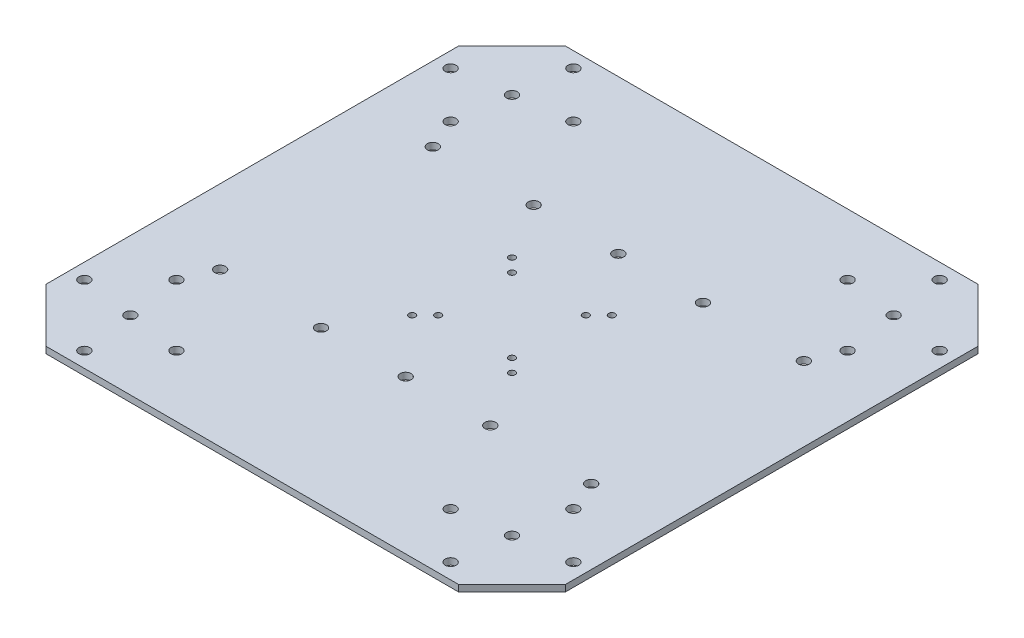
SolidWorks part; units mm, degrees
ref_plane "Front Plane" through (0, 0, 0) normal (0, 0, 1) x (1, 0, 0)
ref_plane "Top Plane" through (0, 0, 0) normal (0, 1, 0) x (1, 0, 0)
ref_plane "Right Plane" through (0, 0, 0) normal (1, 0, 0) x (0, 0, -1)
sketch "Sketch1" plane through (0, 0, 0) normal (0, 1, 0) x (1, 0, 0)
  line L0 (-72.7246, 121.6334) -> (117.2754, 121.6334)
  line L1 (117.2754, 121.6334) -> (142.0241, 96.8847)
  line L2 (142.0241, 96.8847) -> (142.0241, -93.1153)
  line L3 (142.0241, -93.1153) -> (117.2754, -117.864)
  line L4 (117.2754, -117.864) -> (-72.7246, -117.864)
  line L5 (-72.7246, -117.864) -> (-97.4734, -93.1153)
  line L6 (-97.4734, -93.1153) -> (-97.4734, 96.8847)
  line L7 (-97.4734, 96.8847) -> (-72.7246, 121.6334)
  dimension "D1" = 190
  dimension "D2" = 135
  dimension "D3" = 135
  dimension "D4" = 35
extrude "Boss-Extrude1" add sketch "Sketch1" along normal blind 3
sketch "Sketch2" plane through (0, 3, 0) normal (0, 1, 0) x (1, 0, 0)
  line L0 (-97.4734, -93.1153) -> (-58.5825, -54.2244)
  line L1 (-58.5825, -54.2244) -> (-33.8338, -78.9732)
  line L2 (-33.8338, -78.9732) -> (-72.7246, -117.864)
  line L3 (142.0241, -93.1153) -> (106.6439, -53.574)
  line L4 (106.6439, -53.574) -> (80.601, -76.8764)
  line L5 (80.601, -76.8764) -> (117.2754, -117.864)
  line L6 (117.2754, 121.6334) -> (77.828, 85.6472)
  line L7 (77.828, 85.6472) -> (101.3915, 59.8173)
  line L8 (101.3915, 59.8173) -> (142.0241, 96.8847)
  line L9 (-72.7246, 121.6334) -> (-36.0091, 80.6826)
  line L10 (-36.0091, 80.6826) -> (-62.0301, 57.3529)
  line L11 (-62.0301, 57.3529) -> (-97.4734, 96.8847)
  line L12 (-97.4734, -93.1153) -> (-72.7246, -117.864)
  line L13 (117.2754, -117.864) -> (142.0241, -93.1153)
  line L14 (117.2754, 121.6334) -> (142.0241, 96.8847)
  line L15 (-97.4734, 96.8847) -> (-72.7246, 121.6334)
  dimension "D1" = 55
  dimension "D2" = 90
  dimension "D3" = 55
  dimension "D4" = 90
  dimension "D5" = 55
  dimension "D6" = 90
  dimension "D7" = 90
  dimension "D8" = 55
  dimension "D9" = 90
extrude "Boss-Extrude2" add sketch "Sketch2" against normal blind 2
sketch "Sketch3" plane through (0, 3, 0) normal (0, 1, 0) x (1, 0, 0)
  line L0 (142.0241, -93.1153) -> (133.1853, -84.2765)
  line L1 (133.1853, -84.2765) -> (134.953, -82.5087)
  line L2 (134.953, -82.5087) -> (113.7398, -61.2955)
  line L3 (113.7398, -61.2955) -> (85.4556, -89.5798)
  line L4 (85.4556, -89.5798) -> (106.6688, -110.793)
  line L5 (117.2754, 121.6334) -> (108.4365, 112.7946)
  line L6 (108.4365, 112.7946) -> (106.6688, 114.5624)
  line L7 (106.6688, 114.5624) -> (85.4556, 93.3492)
  line L8 (85.4556, 93.3492) -> (113.7398, 65.0649)
  line L9 (113.7398, 65.0649) -> (134.953, 86.2781)
  line L10 (-72.7246, 121.6334) -> (-63.8858, 112.7946)
  line L11 (-63.8858, 112.7946) -> (-62.118, 114.5624)
  line L12 (-62.118, 114.5624) -> (-40.9048, 93.3492)
  line L13 (-40.9048, 93.3492) -> (-69.1891, 65.0649)
  line L14 (-69.1891, 65.0649) -> (-90.4023, 86.2781)
  line L15 (-42.6726, -87.812) -> (-40.9048, -89.5798)
  line L16 (-60.3503, -109.0252) -> (-62.118, -110.793)
  line L17 (-70.9569, -63.0633) -> (-69.1891, -61.2955)
  line L18 (-69.1891, -61.2955) -> (-67.4213, -63.0633)
  line L19 (-40.9048, -89.5798) -> (-42.6726, -91.3475)
  line L20 (-97.4734, -93.1153) -> (-88.6345, -84.2765)
  line L21 (-97.4734, -93.1153) -> (-72.7246, -117.864) construction
  line L22 (-88.6345, -84.2765) -> (-90.4023, -82.5087)
  circle A0 centre (134.953, -82.5087) radius 2.5
  circle A1 centre (113.7398, -61.2955) radius 2.5
  circle A2 centre (85.4556, -89.5798) radius 2.5
  circle A3 centre (106.6688, -110.793) radius 2.5
  circle A4 centre (106.6688, 114.5624) radius 2.5
  circle A5 centre (85.4556, 93.3492) radius 2.5
  circle A6 centre (113.7398, 65.0649) radius 2.5
  circle A7 centre (134.953, 86.2781) radius 2.5
  circle A9 centre (-40.9048, 93.3492) radius 2.5
  circle A10 centre (-69.1891, 65.0649) radius 2.5
  circle A11 centre (-90.4023, 86.2781) radius 2.5
  circle A13 centre (-69.1891, -61.2955) radius 2.5
  circle A14 centre (-40.9048, -89.5798) radius 2.5
  circle A15 centre (-62.118, -110.793) radius 2.5
  circle A16 centre (-62.118, 114.5624) radius 2.5
  circle A17 centre (-90.4023, -82.5087) radius 2.5
  dimension "D3" = 30
  dimension "D6" = 12.5
  dimension "D11" = 12.5
  dimension "D16" = 90
  dimension "D1" = 12.5
  dimension "D2" = 2.5
  dimension "D4" = 40
  dimension "D5" = 30
  dimension "D7" = 2.5
  dimension "D8" = 30
  dimension "D9" = 40
  dimension "D10" = 30
  dimension "D12" = 2.5
  dimension "D13" = 30
  dimension "D14" = 40
  dimension "D15" = 30
  dimension "D17" = 12.5
  dimension "D19" = 40
  dimension "D20" = 30
extrude "Cut-Extrude1" cut sketch "Sketch3" against normal blind 3
sketch "Sketch4" plane through (0, 3, 0) normal (0, 1, 0) x (1, 0, 0)
  line L0 (22.2754, 121.6334) -> (22.2754, 26.8847) construction
  line L1 (117.2754, 121.6334) -> (-72.7246, 121.6334) construction
  line L2 (-72.7246, -117.864) -> (117.2754, -117.864) construction
  line L3 (-97.4734, 1.8847) -> (-2.7246, 1.8847) construction
  line L4 (-97.4734, 96.8847) -> (-97.4734, -93.1153) construction
  line L5 (142.0241, -93.1153) -> (142.0241, 96.8847) construction
  line L6 (47.2754, 1.8847) -> (142.0241, 1.8847) construction
  line L7 (22.2754, -23.1153) -> (22.2754, -117.864) construction
  line L8 (-2.7246, -23.1153) -> (47.2754, -23.1153)
  line L9 (-2.7246, -23.1153) -> (-2.7246, 26.8847)
  line L10 (-2.7246, 26.8847) -> (47.2754, 26.8847)
  line L11 (47.2754, -23.1153) -> (47.2754, 26.8847)
  line L12 (47.2754, 26.8847) -> (45.2754, 24.8847)
  line L13 (45.2754, 24.8847) -> (45.2754, 18.8847)
  line L14 (45.2754, 18.8847) -> (39.2754, 18.8847)
  line L15 (47.2754, -23.1153) -> (45.2754, -21.1153)
  line L16 (45.2754, -21.1153) -> (45.2754, -15.1153)
  line L17 (45.2754, -15.1153) -> (39.2754, -15.1153)
  line L18 (-2.7246, -23.1153) -> (-0.7246, -21.1153)
  line L19 (-0.7246, -21.1153) -> (-0.7246, -15.1153)
  line L20 (-0.7246, -15.1153) -> (5.2754, -15.1153)
  line L21 (-2.7246, 26.8847) -> (-0.7246, 24.8847)
  line L22 (-0.7246, 24.8847) -> (5.2754, 24.8847)
  line L23 (5.2754, 24.8847) -> (5.2754, 18.8847)
  circle A1 centre (45.2754, 24.8847) radius 1.5
  circle A2 centre (39.2754, 18.8847) radius 1.5
  circle A3 centre (45.2754, -21.1153) radius 1.5
  circle A4 centre (39.2754, -15.1153) radius 1.5
  circle A5 centre (-0.7246, -21.1153) radius 1.5
  circle A6 centre (5.2754, -15.1153) radius 1.5
  circle A7 centre (-0.7246, 24.8847) radius 1.5
  circle A8 centre (5.2754, 18.8847) radius 1.5
  dimension "D4" = 2
  dimension "D6" = 6
  dimension "D5" = 3
  dimension "D8" = 3
  dimension "D11" = 3
  dimension "D14" = 3
  dimension "D17" = 3
  dimension "D19" = 3
  dimension "D22" = 3
  dimension "D23" = 3
  dimension "D1" = 50
  dimension "D2" = 50
  dimension "D3" = 2
  dimension "D7" = 6
  dimension "D9" = 2
  dimension "D10" = 2
  dimension "D12" = 6
  dimension "D13" = 6
  dimension "D15" = 2
  dimension "D16" = 2
  dimension "D18" = 6
  dimension "D20" = 2
  dimension "D21" = 2
extrude "Cut-Extrude2" cut sketch "Sketch4" against normal blind 10
sketch "Sketch5" plane through (0, 3, 0) normal (0, 1, 0) x (1, 0, 0)
  line L0 (-85.099, 109.2591) -> (-45.8172, 69.9773) construction
  line L1 (-72.7246, 121.6334) -> (-97.4734, 96.8847) construction
  line L2 (-69.1891, 65.0649) -> (-90.4023, 86.2781) construction
  line L3 (-79.7957, 75.6715) -> (-65.6536, 89.8136) construction
  line L4 (129.6497, 109.2591) -> (80.8546, 60.464) construction
  line L5 (142.0241, 96.8847) -> (117.2754, 121.6334) construction
  line L6 (85.4556, 93.3492) -> (106.6688, 114.5624) construction
  line L7 (96.0622, 103.9558) -> (110.2043, 89.8136) construction
  line L8 (129.6497, -105.4897) -> (80.8546, -56.6946) construction
  line L9 (117.2754, -117.864) -> (142.0241, -93.1153) construction
  line L10 (134.953, -82.5087) -> (113.7398, -61.2955) construction
  line L11 (124.3464, -71.9021) -> (110.2043, -86.0442) construction
  line L12 (-85.099, -105.4897) -> (-40.1291, -60.5197) construction
  line L13 (-97.4734, -93.1153) -> (-72.7246, -117.864) construction
  line L14 (-90.4023, -82.5087) -> (-69.1891, -61.2955) construction
  line L15 (-79.7957, -71.9021) -> (-65.6536, -86.0442) construction
  circle A0 centre (-65.6536, 89.8136) radius 2.5
  circle A1 centre (110.2043, 89.8136) radius 2.5
  circle A2 centre (110.2043, -86.0442) radius 2.5
  circle A3 centre (-65.6536, -86.0442) radius 2.5
  dimension "D1" = 5
  dimension "D2" = 5
  dimension "D3" = 5
  dimension "D4" = 5
extrude "Cut-Extrude3" cut sketch "Sketch5" against normal blind 4
sketch "Sketch6" plane through (0, 3, 0) normal (0, 1, 0) x (1, 0, 0)
  line L0 (22.2754, 121.6334) -> (22.2754, -117.864) construction
  line L1 (117.2754, 121.6334) -> (-72.7246, 121.6334) construction
  line L2 (-72.7246, -117.864) -> (117.2754, -117.864) construction
  line L3 (-16.7246, -47.1153) -> (-16.7246, -49.6153) construction
  line L10 (-16.7246, -47.1153) -> (61.2754, -47.1153)
  line L11 (-16.7246, -47.1153) -> (-16.7246, 50.8847)
  line L12 (-16.7246, 50.8847) -> (61.2754, 50.8847)
  line L13 (61.2754, -47.1153) -> (61.2754, 50.8847)
  line L14 (-16.7246, -47.1153) -> (61.2754, 50.8847) construction
  line L15 (-16.7246, 50.8847) -> (61.2754, -47.1153) construction
  line L16 (-16.7246, -47.1153) -> (-63.2246, -47.1153) construction
  line L17 (-16.7246, 50.8847) -> (-63.2246, 50.8847) construction
  circle A0 centre (-16.7246, 50.8847) radius 2.5
  circle A1 centre (61.2754, 50.8847) radius 2.5
  circle A2 centre (61.2754, -47.1153) radius 2.5
  circle A3 centre (-16.7246, -47.1153) radius 2.5
  circle A10 centre (-63.2246, -47.1153) radius 2.5
  circle A11 centre (-63.2246, 50.8847) radius 2.5
  circle A12 centre (107.7754, -47.1153) radius 2.5
  circle A13 centre (107.7754, 50.8847) radius 2.5
  circle A14 centre (22.2754, -47.1153) radius 2.5
  circle A15 centre (22.2754, 50.8847) radius 2.5
  point P6 (22.2754, 1.8847)
  dimension "D3" = 5
  dimension "D5" = 5
  dimension "D8" = 46.5
  dimension "D9" = 5
  dimension "D4" = 5
  dimension "D1" = 98
  dimension "D2" = 78
  dimension "D10" = 2
extrude "Cut-Extrude6" cut sketch "Sketch6" against normal through all contours A10 | A11 | A13 | A12 | A2 | A14 | A3 | A0 | A15 | A1
